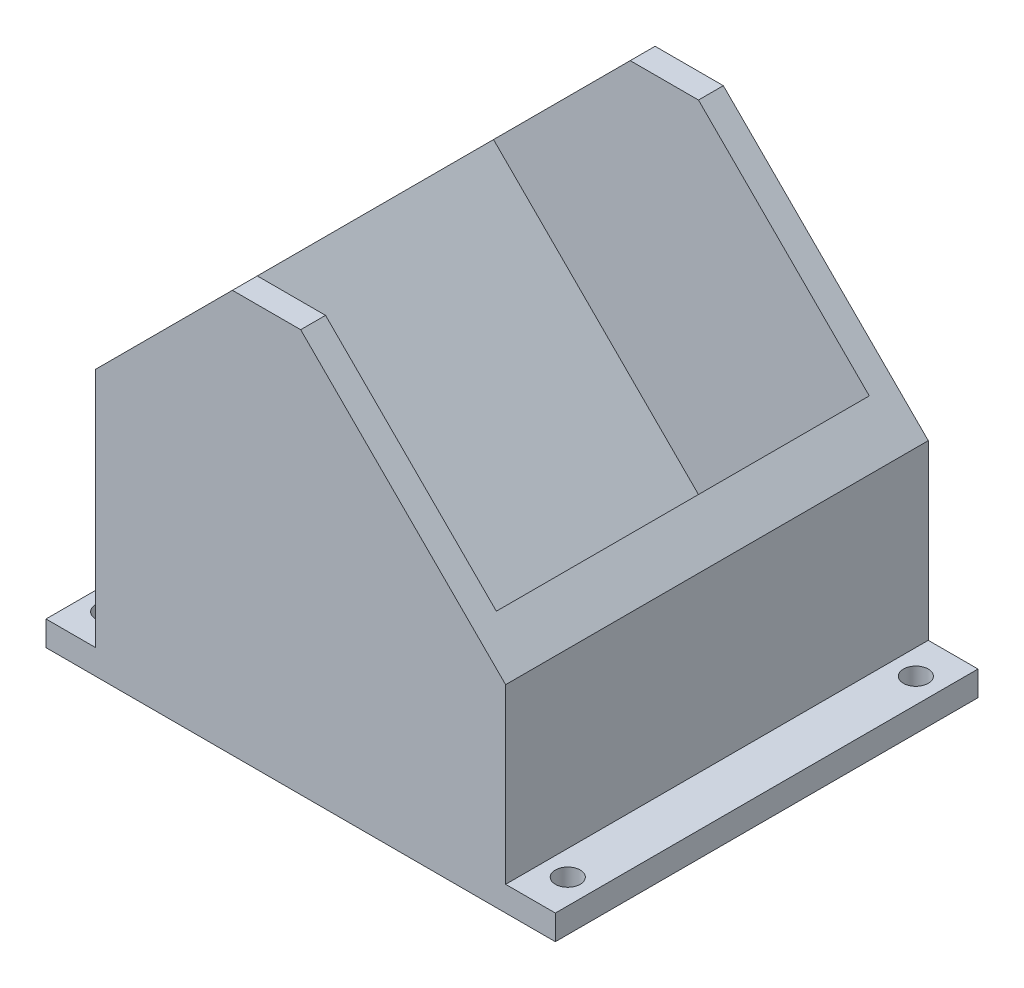
SolidWorks part; units mm, degrees
ref_plane "Front Plane" through (0, 0, 0) normal (0, 0, 1) x (1, 0, 0)
ref_plane "Top Plane" through (0, 0, 0) normal (0, 1, 0) x (1, 0, 0)
ref_plane "Right Plane" through (0, 0, 0) normal (1, 0, 0) x (0, 0, -1)
sketch "Sketch2" plane through (0, 0, 0) normal (0, 0, 1) x (1, 0, 0)
  line L0 (0, 0) -> (-97, 0)
  line L1 (-97, 0) -> (-97, 107)
  line L2 (-97, 107) -> (0, 10)
  line L3 (0, 10) -> (0, 0)
  dimension "D1" = 97
  dimension "D2" = 45
  dimension "D3" = 10
extrude "Boss-Extrude1" add sketch "Sketch2" along normal blind 150
sketch "Sketch3" plane through (0, 0, 0) normal (0, -1, 0) x (1, 0, 0)
  line L0 (-48.5, 150) -> (-48.5, 0) construction
  line L1 (-97, 150) -> (0, 150) construction
  line L2 (-97, 0) -> (0, 0) construction
  point P6 (-48.5, 75)
sketch "Sketch4" plane through (0, 0, 150) normal (0, 0, 1) x (1, 0, 0)
  line L0 (-14.5664, 24.5664) -> (67.8672, 107)
  line L1 (0, 10) -> (-97, 107) construction
  line L2 (67.8672, 107) -> (67.8672, 0)
  line L3 (67.8672, 0) -> (0, 0)
  line L4 (-14.5664, 24.5664) -> (0, 10)
  line L5 (0, 10) -> (0, 0)
  dimension "D1" = 90
  dimension "D3" = 20.6
extrude "Boss-Extrude2" add sketch "Sketch4" against normal up to surface (150 mm away) up to face at (-48.5, 29.25, 0)
sketch "Sketch5" plane through (0, 0, 0) normal (0, -1, 0) x (1, 0, 0)
  line L0 (-14.5664, 150) -> (-14.5664, 0) construction
  line L1 (-97, 150) -> (67.8672, 150) construction
sketch "Sketch6" plane through (0, 0, 0) normal (0, 1, 0) x (1, 0, 0)
  line L0 (67.8672, 0) -> (67.8672, -150) construction
  line L1 (-97, -150) -> (67.8672, -150)
  line L2 (-97, -150) -> (-97, -160)
  line L3 (-97, -160) -> (67.8672, -160)
  line L4 (67.8672, -150) -> (67.8672, -160)
  line L6 (-97, 0) -> (67.8672, 0)
  line L7 (-97, 0) -> (-97, 10)
  line L8 (-97, 10) -> (67.8672, 10)
  line L9 (67.8672, 0) -> (67.8672, 10)
  dimension "D1" = 10
  dimension "D2" = 10
extrude "Boss-Extrude4" add sketch "Sketch6" along normal up to vertex (107 mm away)
sketch "Sketch7" plane through (0, 0, 160) normal (0, 0, 1) x (1, 0, 0)
  line L0 (-97, 107) -> (-14.5664, 189.4336)
  line L1 (-14.5664, 189.4336) -> (67.8672, 107)
  line L2 (67.8672, 107) -> (-97, 107)
  dimension "D1" = 45
  dimension "D2" = 45
extrude "Boss-Extrude5" add sketch "Sketch7" against normal up to surface (10 mm away) up to face at (-14.5664, 79.5221, 150)
sketch "Sketch8" plane through (0, 0, -10) normal (0, 0, -1) x (-1, 0, 0)
  line L0 (-67.8672, 107) -> (97, 107)
  line L4 (14.5664, 24.5664) -> (97, 107)
  line L5 (97, 107) -> (14.5664, 189.4336)
  line L6 (14.5664, 189.4336) -> (-67.8672, 107)
  line L7 (-67.8672, 107) -> (14.5664, 24.5664)
  line L9 (97, 107) -> (14.5664, 189.4336)
  line L10 (14.5664, 189.4336) -> (-67.8672, 107)
  dimension "D1" = 0
extrude "Boss-Extrude6" add sketch "Sketch8" against normal up to surface (10 mm away) up to face at (-14.5664, 79.5221, 0)
sketch "Sketch9" plane through (0, 0, 0) normal (0, 1, 0) x (1, 0, 0)
  line L0 (-14.5664, -160) -> (-97, -160) construction
  line L1 (-97, 10) -> (-117, 10)
  line L2 (-97, 10) -> (-97, -160)
  line L3 (-97, -160) -> (-117, -160)
  line L4 (-117, 10) -> (-117, -160)
  line L5 (-14.5664, 0) -> (-14.5664, -150) construction
  line L6 (67.8672, -160) -> (87.8672, -160)
  line L7 (87.8672, 10) -> (87.8672, -160)
  line L8 (67.8672, 10) -> (87.8672, 10)
  line L9 (67.8672, 10) -> (67.8672, -160)
  circle A0 centre (-107, -145) radius 5
  circle A1 centre (-107, -5) radius 5
  circle A2 centre (77.8672, -145) radius 5
  circle A3 centre (77.8672, -5) radius 5
  point P12 (-107, -160)
  dimension "D4" = 10
  dimension "D5" = 10
  dimension "D1" = 20
  dimension "D2" = 15
  dimension "D3" = 15
extrude "Boss-Extrude7" add sketch "Sketch9" along normal blind 10
sketch "Sketch10" plane through (0, 0, 160) normal (0, 0, 1) x (1, 0, 0)
  line L0 (67.8672, 107) -> (-14.5664, 189.4336) construction
  line L1 (-18.1019, 185.8981) -> (67.8672, 99.9289) construction
  line L2 (-14.5664, 189.4336) -> (-97, 107) construction
  line L3 (67.8672, 107) -> (67.8672, 10) construction
  circle A0 centre (10.1823, 157.6138) radius 3.5
  circle A1 centre (53.7251, 114.0711) radius 3.5
  dimension "D1" = 7
  dimension "D2" = 7
  dimension "D3" = 5
  dimension "D4" = 5
  dimension "D5" = 40
  dimension "D6" = 20
extrude "Cut-Extrude1" [suppressed] cut sketch "Sketch10" against normal through all
sketch "Sketch11" [suppressed] plane through (0, 0, 0) normal (0, 0, 1) x (1, 0, 0)
  circle A0 centre (10.1823, 167.6138) radius 3.5 construction
  circle A1 centre (10.1823, 167.6138) radius 3.5
extrude "Boss-Extrude8" [suppressed] add sketch "Sketch11" against normal up to surface (10 mm away)
sketch "Sketch12" plane through (0, 0, 160) normal (0, 0, 1) x (1, 0, 0)
  line L0 (-42.02, 161.98) -> (12.8872, 161.98)
  line L1 (-14.5664, 189.4336) -> (-97, 107) construction
  line L2 (67.8672, 107) -> (-14.5664, 189.4336) construction
  line L3 (-42.02, 161.98) -> (-14.5664, 189.4336)
  line L4 (-14.5664, 189.4336) -> (12.8872, 161.98)
  dimension "D1" = 54.98
extrude "Cut-Extrude2" cut sketch "Sketch12" against normal through all both and the other way through all
sketch "Sketch14" plane through (0, 0, 160) normal (0, 0, 1) x (1, 0, 0)
  line L0 (-14.5664, 161.98) -> (67.8672, 79.5464)
  line L1 (12.8872, 161.98) -> (-42.02, 161.98) construction
  line L2 (67.8672, 107) -> (67.8672, 10) construction
  line L3 (67.8672, 107) -> (12.8872, 161.98) construction
  line L4 (-14.5664, 161.98) -> (12.8872, 161.98)
  line L5 (12.8872, 161.98) -> (67.8672, 107)
  line L6 (67.8672, 107) -> (67.8672, 79.5464)
extrude "Cut-Extrude3" cut sketch "Sketch14" against normal through all both and the other way through all
